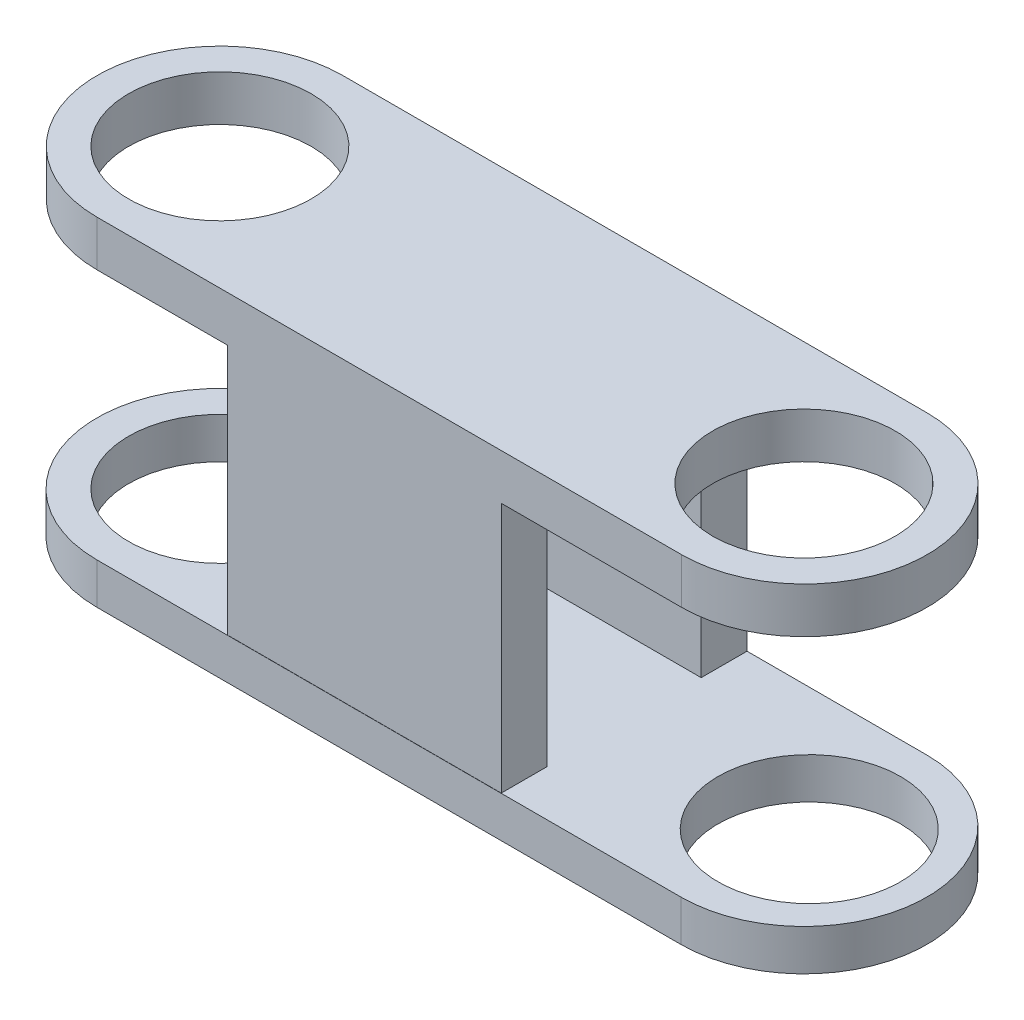
SolidWorks part; units mm, degrees
ref_plane "Alzado" through (0, 0, 0) normal (0, 0, 1) x (1, 0, 0)
ref_plane "Planta" through (0, 0, 0) normal (0, 1, 0) x (1, 0, 0)
ref_plane "Vista lateral" through (0, 0, 0) normal (1, 0, 0) x (0, 0, -1)
sketch "Croquis1" plane through (0, 0, 0) normal (0, 1, 0) x (1, 0, 0)
  line L0 (0, 0) -> (128.0795, 0) construction
  line L1 (0, 26.9043) -> (128.0795, 26.9043)
  line L2 (0, -26.9043) -> (128.0795, -26.9043)
  arc A0 (0, 26.9043) -> (0, -26.9043) centre (0, 0) ccw
  arc A1 (128.0795, -26.9043) -> (128.0795, 26.9043) centre (128.0795, 0) ccw
  point P3 (64.0398, 0)
extrude "Saliente-Extruir1" add sketch "Croquis1" along normal blind 10
sketch "Croquis2" plane through (0, 0, 0) normal (0, -1, 0) x (1, 0, 0)
  circle A0 centre (0, 0) radius 20
  dimension "D1" = 40
extrude "Cortar-Extruir1" cut sketch "Croquis2" against normal blind 10
sketch "Croquis3" plane through (0, 10, 0) normal (0, 1, 0) x (1, 0, 0)
  circle A0 centre (127.9803, 0) radius 20
  dimension "D1" = 40
extrude "Cortar-Extruir2" cut sketch "Croquis3" against normal blind 10
sketch "Croquis5" plane through (0, 0, 0) normal (0, -1, 0) x (-1, 0, 0)
  line L0 (0, -26.9043) -> (-128.0795, -26.9043) construction
  line L1 (-28.5585, -26.9043) -> (-88.5585, -26.9043)
  line L2 (-28.5585, -26.9043) -> (-28.5585, -16.9043)
  line L3 (-28.5585, -16.9043) -> (-88.5585, -16.9043)
  line L4 (-88.5585, -26.9043) -> (-88.5585, -16.9043)
  line L5 (-128.0795, 26.9043) -> (0, 26.9043) construction
  line L6 (-28.5585, 26.9043) -> (-88.5585, 26.9043)
  line L7 (-28.5585, 26.9043) -> (-28.5585, 16.9043)
  line L8 (-28.5585, 16.9043) -> (-88.5585, 16.9043)
  line L9 (-88.5585, 26.9043) -> (-88.5585, 16.9043)
  dimension "D1" = 10
  dimension "D2" = 10
  dimension "D3" = 60
  dimension "D4" = 60
extrude "Saliente-Extruir3" add sketch "Croquis5" along normal blind 55
sketch "Croquis7" plane through (0, -55, 0) normal (0, -1, 0) x (-1, 0, 0)
  line L0 (0, 0) -> (-127.9803, 0) construction
  line L1 (0, -26.9507) -> (-127.9803, -26.9507)
  line L2 (0, 26.9507) -> (-127.9803, 26.9507)
  arc A0 (0, -26.9507) -> (0, 26.9507) centre (0, 0) ccw
  arc A1 (-127.9803, 26.9507) -> (-127.9803, -26.9507) centre (-127.9803, 0) ccw
  point P4 (-63.9902, 0)
extrude "Saliente-Extruir4" add sketch "Croquis7" along normal blind 9
sketch "Croquis8" plane through (0, -64, 0) normal (0, -1, 0) x (-1, 0, 0)
  circle A0 centre (-129.14, 0) radius 20
  dimension "D1" = 40
extrude "Cortar-Extruir3" cut sketch "Croquis8" against normal blind 9
sketch "Croquis9" plane through (0, -64, 0) normal (0, -1, 0) x (-1, 0, 0)
  circle A0 centre (0, 0) radius 20
  dimension "D1" = 40
extrude "Cortar-Extruir4" cut sketch "Croquis9" against normal blind 10
